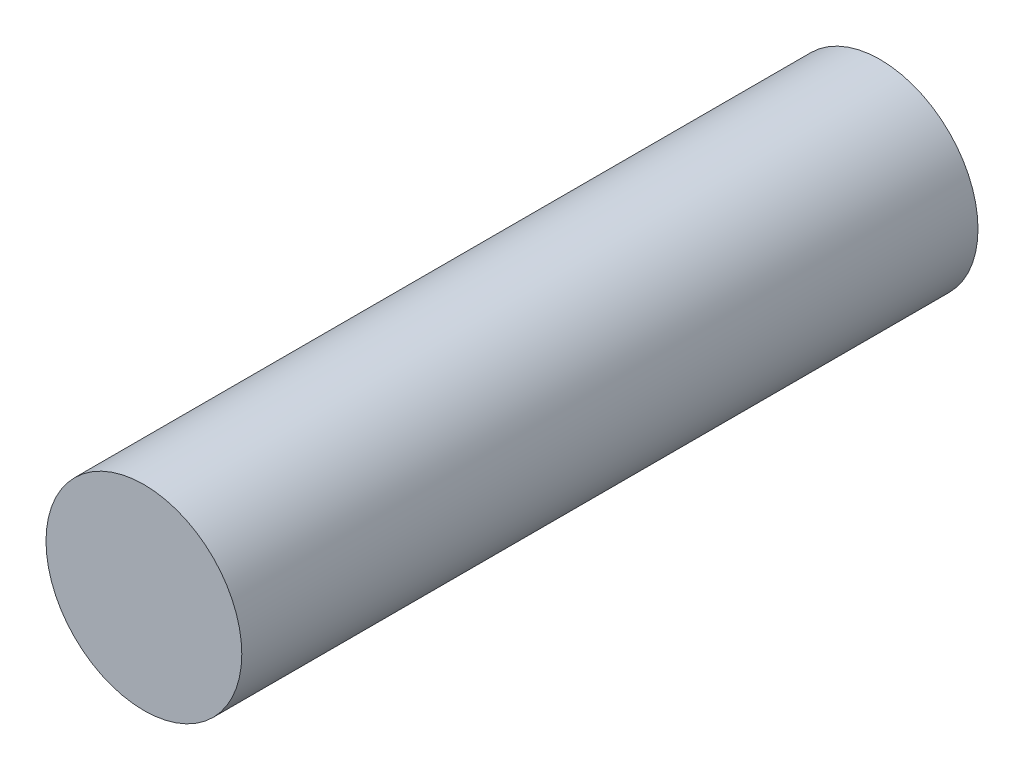
SolidWorks part; units mm, degrees
ref_plane "Front Plane" through (0, 0, 0) normal (0, 0, 1) x (1, 0, 0)
ref_plane "Top Plane" through (0, 0, 0) normal (0, 1, 0) x (1, 0, 0)
ref_plane "Right Plane" through (0, 0, 0) normal (1, 0, 0) x (0, 0, -1)
sketch "Sketch1" plane through (0, 0, 0) normal (0, 0, 1) x (1, 0, 0)
  circle A0 centre (0, 0) radius 6.42
  dimension "D1" = 12.84
extrude "Boss-Extrude1" add sketch "Sketch1" along normal blind 48.28
